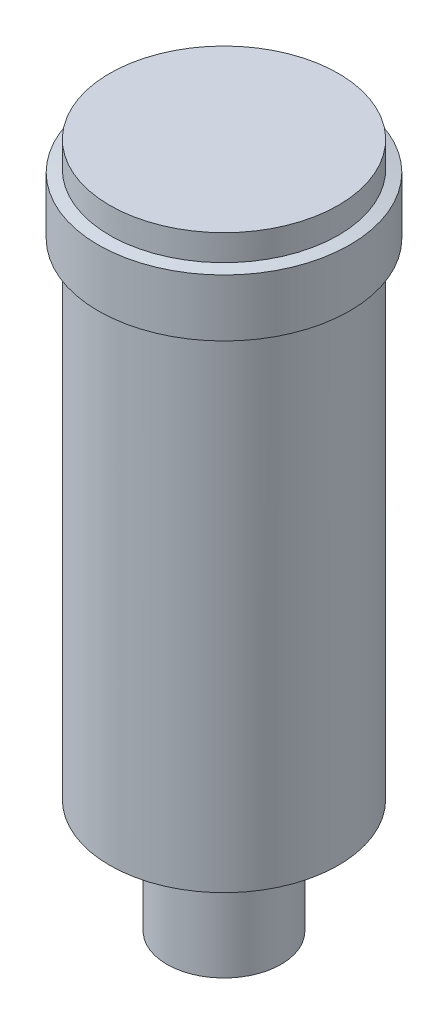
SolidWorks part; units mm, degrees
ref_plane "前视基准面" through (0, 0, 0) normal (0, 0, 1) x (1, 0, 0)
ref_plane "上视基准面" through (0, 0, 0) normal (0, 1, 0) x (1, 0, 0)
ref_plane "右视基准面" through (0, 0, 0) normal (1, 0, 0) x (0, 0, -1)
other "Configuration Table"
sketch "草图1" plane through (0, 0, 0) normal (0, 1, 0) x (1, 0, 0)
  circle A0 centre (0, 0) radius 1
  dimension "D1" = 2
extrude "凸台-拉伸1" add sketch "草图1" along normal blind 2
sketch "草图2" plane through (0, 2, 0) normal (0, 1, 0) x (1, 0, 0)
  circle A0 centre (0, 0) radius 2
  dimension "D1" = 4
extrude "凸台-拉伸2" add sketch "草图2" along normal blind 10
sketch "草图3" plane through (0, 0, 0) normal (0, 0, 1) x (1, 0, 0)
  line L0 (0, 12) -> (0, 10)
  line L1 (2, 12) -> (-2, 12) construction
  line L2 (0, 11) -> (2.2, 11) construction
  line L3 (2.2, 11.5) -> (2.2, 10.5)
  line L4 (2.2, 11.5) -> (0, 12)
  line L5 (2.2, 10.5) -> (0, 10)
  line L6 (0, 11) -> (0, 0) construction
  point P10 (2.2, 11)
  dimension "D1" = 2
  dimension "D2" = 2.2
  dimension "D3" = 0.5
revolve "旋转1" add sketch "草图3" angle 360 about L0
